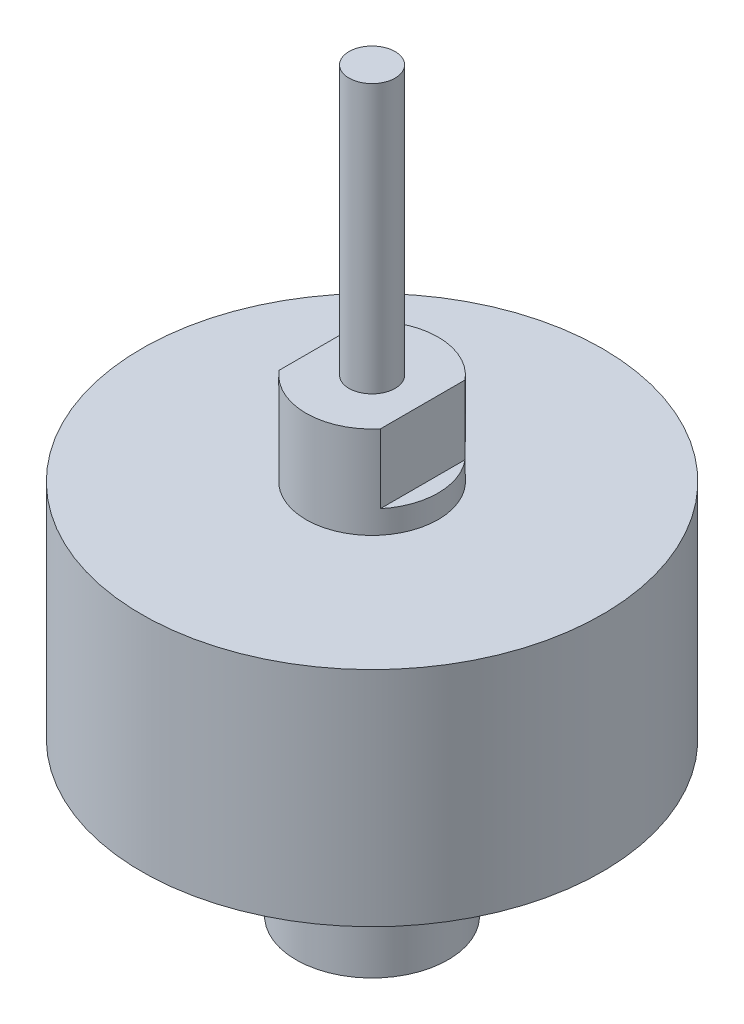
SolidWorks part; units mm, degrees
ref_plane "Front Plane" through (0, 0, 0) normal (0, 0, 1) x (1, 0, 0)
ref_plane "Top Plane" through (0, 0, 0) normal (0, 1, 0) x (1, 0, 0)
ref_plane "Right Plane" through (0, 0, 0) normal (1, 0, 0) x (0, 0, -1)
sketch "Sketch1" plane through (0, 0, 0) normal (0, 1, 0) x (1, 0, 0)
  circle A0 centre (0, 0) radius 4.95
  dimension "D1" = 9.9
extrude "Boss-Extrude1" add sketch "Sketch1" along normal blind 6
sketch "Sketch2" plane through (0, 6, 0) normal (0, 1, 0) x (1, 0, 0)
  circle A0 centre (0, 0) radius 5.5
  dimension "D1" = 11
extrude "Boss-Extrude2" add sketch "Sketch2" along normal blind 4
sketch "Sketch3" plane through (0, 10, 0) normal (0, 1, 0) x (1, 0, 0)
  circle A0 centre (0, 0) radius 15
  dimension "D1" = 30
extrude "Boss-Extrude3" add sketch "Sketch3" along normal blind 14.5
sketch "Sketch4" plane through (0, 24.5, 0) normal (0, 1, 0) x (1, 0, 0)
  circle A0 centre (0, 0) radius 4.3
  dimension "D1" = 8.6
extrude "Boss-Extrude4" add sketch "Sketch4" along normal blind 1.5
sketch "Sketch5" plane through (0, 26, 0) normal (0, 1, 0) x (1, 0, 0)
  line L0 (-3.3, 2.7568) -> (-3.3, -2.7568)
  line L1 (3.3, 2.7568) -> (3.3, -2.7568)
  circle A0 centre (0, 0) radius 4.3 construction
  arc A1 (3.3, 2.7568) -> (-3.3, 2.7568) centre (0, 0) ccw
  circle A2 centre (0, 0) radius 4.3
  arc A3 (-3.3, -2.7568) -> (3.3, -2.7568) centre (0, 0) ccw
  dimension "D1" = 6.6
  dimension "D2" = 0
extrude "Boss-Extrude5" add sketch "Sketch5" along normal blind 4.5
sketch "Sketch6" plane through (0, 30.5, 0) normal (0, 1, 0) x (1, 0, 0)
  circle A0 centre (0, 0) radius 1.5
  dimension "D1" = 3
extrude "Boss-Extrude6" add sketch "Sketch6" along normal blind 17.5
